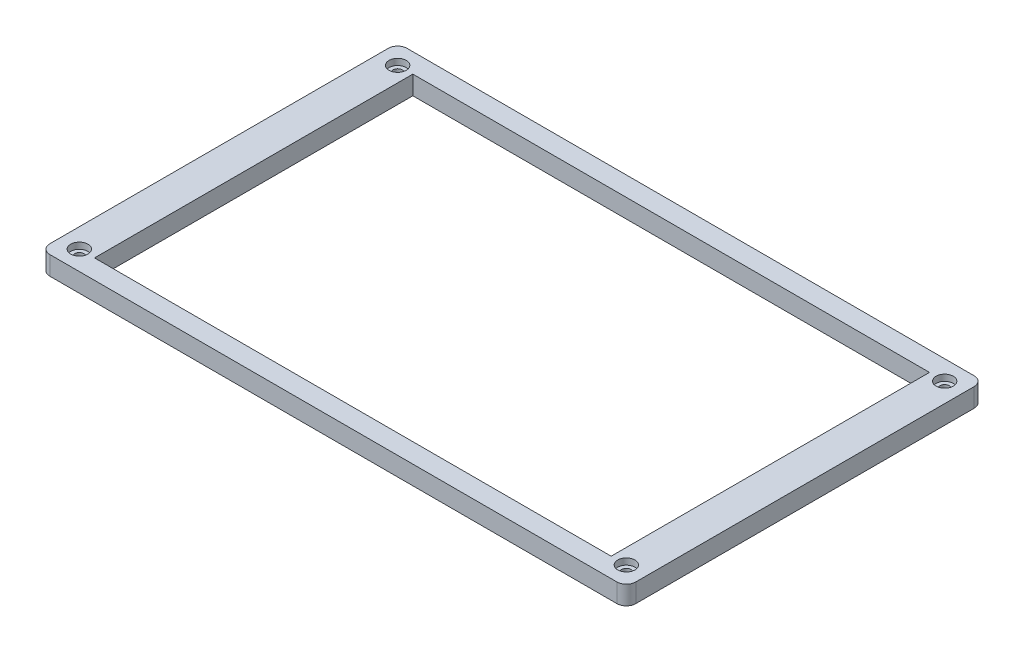
SolidWorks part; units mm, degrees
ref_plane "前视基准面" through (0, 0, 0) normal (0, 0, 1) x (1, 0, 0)
ref_plane "上视基准面" through (0, 0, 0) normal (0, 1, 0) x (1, 0, 0)
ref_plane "右视基准面" through (0, 0, 0) normal (1, 0, 0) x (0, 0, -1)
sketch "草图1" plane through (0, 0, 0) normal (0, 1, 0) x (1, 0, 0)
  line L1 (-93.2998, 61.0653) -> (93.7002, 61.0653)
  line L2 (-93.2998, 61.0653) -> (-93.2998, -52.9347)
  line L3 (-93.2998, -52.9347) -> (93.7002, -52.9347)
  line L4 (93.7002, 61.0653) -> (93.7002, -52.9347)
  dimension "D1" = 187
  dimension "D2" = 114
extrude "凸台-拉伸1" add sketch "草图1" along normal blind 6
fillet "圆角1" radius 3 4 edges at (-93.2998, 3, -61.0653) (93.7002, 3, -61.0653) (93.7002, 3, 52.9347) (-93.2998, 3, 52.9347)
sketch "草图3" plane through (0, 6, 0) normal (0, 1, 0) x (1, 0, 0)
  line L1 (-82.2494, 54.8653) -> (82.6506, 54.8653)
  line L2 (-82.2494, 54.8653) -> (-82.2494, -46.7347)
  line L3 (-82.2494, -46.7347) -> (82.6506, -46.7347)
  line L4 (82.6506, 54.8653) -> (82.6506, -46.7347)
extrude "切除-拉伸1" cut sketch "草图3" against normal blind 6
sketch "草图6" plane through (0, 6, 0) normal (0, 1, 0) x (1, 0, 0)
  line L0 (0.2002, 61.0653) -> (0.2002, -61.9861) construction
  line L1 (90.7002, 61.0653) -> (-90.2998, 61.0653) construction
  line L2 (93.7002, 4.0653) -> (-101.1902, 4.0653) construction
  line L3 (93.7002, -49.9347) -> (93.7002, 58.0653) construction
  circle A0 centre (87.5006, -46.7349) radius 1.5
  circle A1 centre (87.5006, 54.8655) radius 1.5
  circle A2 centre (-87.1001, -46.7349) radius 1.5
  circle A3 centre (-87.1001, 54.8655) radius 1.5
  dimension "D1" = 3
extrude "切除-拉伸3" cut sketch "草图6" against normal blind 6
sketch "草图7" plane through (0, 6, 0) normal (0, 1, 0) x (1, 0, 0)
  line L0 (-90.2994, 4.0653) -> (102.3294, 4.0653) construction
  line L1 (-90.2994, 54.8653) -> (-90.2994, -46.7347) construction
  line L2 (0.2002, -52.9347) -> (0.2002, 83.5466) construction
  line L3 (-90.2998, -52.9347) -> (90.7002, -52.9347) construction
  circle A0 centre (-87.0998, 54.8653) radius 2.75
  circle A1 centre (87.5002, 54.8653) radius 2.75
  circle A2 centre (-87.0998, -46.7347) radius 2.75
  circle A3 centre (87.5002, -46.7347) radius 2.75
  dimension "D1" = 5.5
extrude "切除-拉伸4" cut sketch "草图7" against normal blind 2
